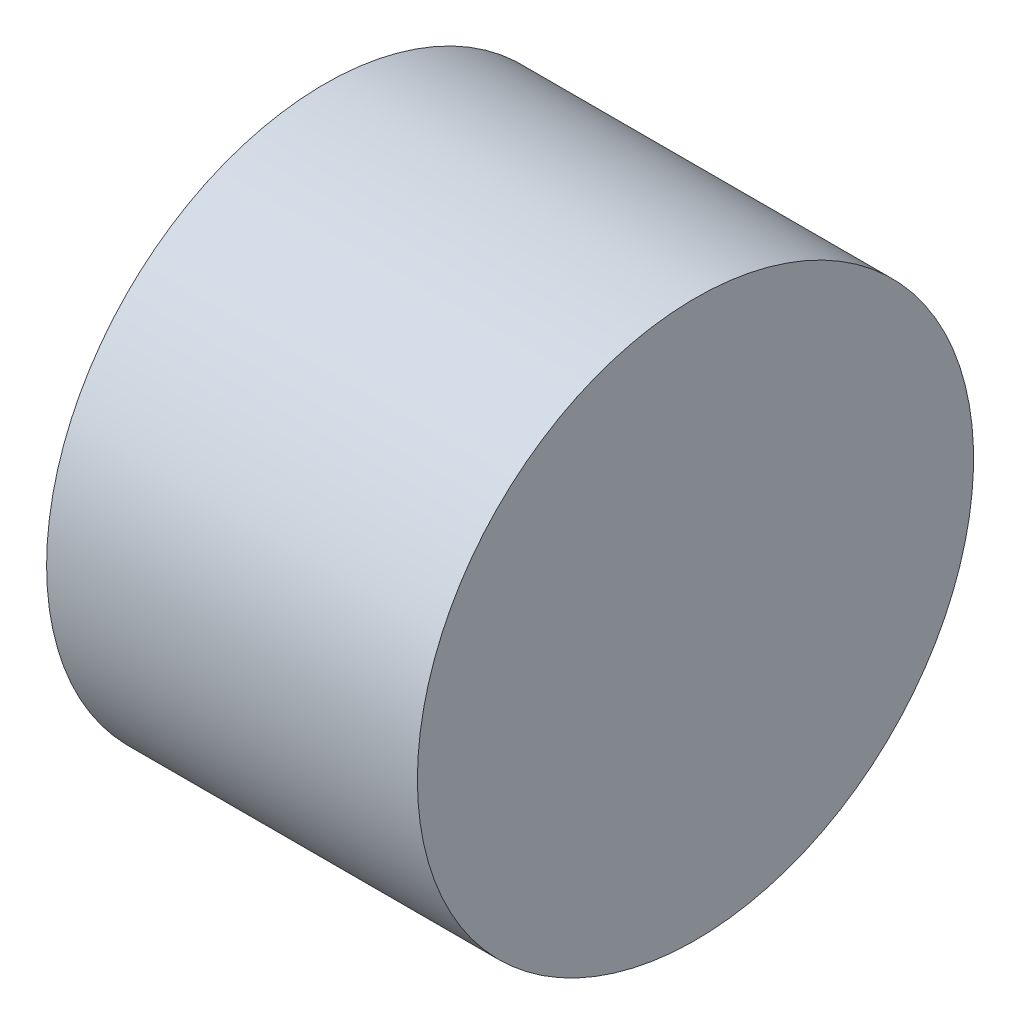
SolidWorks part; units mm, degrees
ref_plane "Спереди" through (0, 0, 0) normal (0, 0, 1) x (1, 0, 0)
ref_plane "Сверху" through (0, 0, 0) normal (0, 1, 0) x (1, 0, 0)
ref_plane "Справа" through (0, 0, 0) normal (1, 0, 0) x (0, 0, -1)
sketch "Эскиз1" plane through (0, 0, 0) normal (0, 0, 1) x (1, 0, 0)
  line L0 (0, 0) -> (14.8571, 0) construction
  line L2 (0, 0) -> (8, 0)
  line L3 (0, 0) -> (0, 6)
  line L4 (0, 6) -> (8, 6)
  line L5 (8, 0) -> (8, 6)
  dimension "D1" = 8
  dimension "D2" = 12
revolve "Повернуть1" add sketch "Эскиз1" angle 360 about L0
